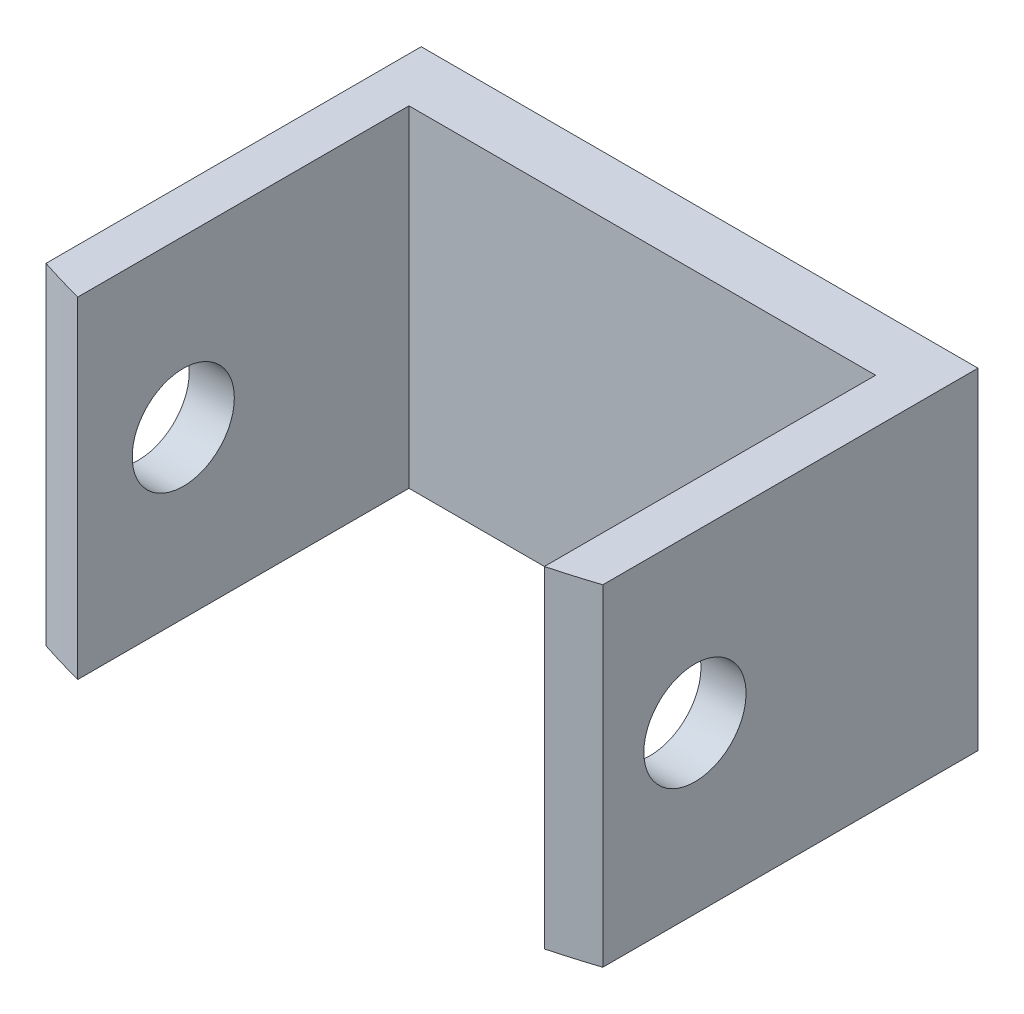
SolidWorks part; units mm, degrees
ref_plane "Front Plane" through (0, 0, 0) normal (0, 0, 1) x (1, 0, 0)
ref_plane "Top Plane" through (0, 0, 0) normal (0, 1, 0) x (1, 0, 0)
ref_plane "Right Plane" through (0, 0, 0) normal (1, 0, 0) x (0, 0, -1)
sketch "Sketch2" plane through (0, 0, 0) normal (0, 1, 0) x (1, 0, 0)
  line L0 (0, 0) -> (0, -76.2) construction
  line L1 (-38.1, -65.9911) -> (0, 0)
  line L2 (0, 0) -> (0, -76.2)
  arc A0 (0, -76.2) -> (-38.1, -65.9911) centre (0, 0) cw
  dimension "D1" = 76.2
extrude "Boss-Extrude1" add sketch "Sketch2" along normal blind 28
sketch "Sketch3" plane through (0, 0, 0) normal (0, 1, 0) x (1, 0, 0)
  line L0 (-38.1, -65.9911) -> (0, -76.2) construction
  line L7 (0, 0) -> (-19.05, -71.0956) construction
  line L8 (-19.05, -71.0956) -> (-19.722, -73.6035) construction
  line L10 (-19.722, -73.6035) -> (19.722, -73.6035) construction
  line L11 (19.722, -73.6035) -> (53.8815, -53.8815) construction
  line L12 (53.8815, -53.8815) -> (73.6035, -19.722) construction
  line L13 (73.6035, -19.722) -> (73.6035, 19.722) construction
  line L14 (73.6035, 19.722) -> (53.8815, 53.8815) construction
  line L15 (53.8815, 53.8815) -> (19.722, 73.6035) construction
  line L16 (19.722, 73.6035) -> (-19.722, 73.6035) construction
  line L17 (-19.722, 73.6035) -> (-53.8815, 53.8815) construction
  line L18 (-53.8815, 53.8815) -> (-73.6035, 19.722) construction
  line L19 (-73.6035, 19.722) -> (-73.6035, -19.722) construction
  line L20 (-73.6035, -19.722) -> (-53.8815, -53.8815) construction
  line L21 (-53.8815, -53.8815) -> (-19.722, -73.6035) construction
  circle A0 centre (0, 0) radius 76.2 construction
  circle A1 centre (0, 0) radius 76.2 construction
sketch "Sketch4" plane through (0, 28, 0) normal (0, 1, 0) x (1, 0, 0)
  line L2 (-19.722, -73.6035) -> (-19.722, -45.6036)
  line L3 (-19.722, -45.6036) -> (19.722, -45.6036)
  line L4 (19.722, -73.6035) -> (19.722, -45.6036)
  line L7 (-19.722, -73.6035) -> (-19.722, -89.0834)
  line L8 (-19.722, -89.0834) -> (19.722, -89.0834)
  line L9 (19.722, -73.6035) -> (19.722, -89.0834)
  dimension "D1" = 28
  dimension "D2" = 39.444
extrude "Cut-Extrude1" cut sketch "Sketch4" against normal through all both and the other way through all
sketch "Sketch5" plane through (-19.722, 0, 0) normal (1, 0, 0) x (0, 0, -1)
  line L0 (-73.6035, 28) -> (-45.6036, 0) construction
  line L1 (-45.6036, 28) -> (-73.6035, 0) construction
  line L3 (-59.6036, 14) -> (-64.6836, 14) construction
  circle A2 centre (-64.6836, 14) radius 6.35
  dimension "D2" = 12.7
  dimension "D1" = 5.08
extrude "Cut-Extrude2" cut sketch "Sketch5" against normal blind 4.572
sketch "Sketch6" plane through (-24.294, 0, 0) normal (1, 0, 0) x (0, 0, -1)
  line L0 (-68.3666, 14) -> (-68.4936, 14) construction
  line L1 (-71.0336, 14) -> (-70.7796, 14) construction
  line L2 (-64.6836, 17.81) -> (-64.6836, 20.096) construction
  line L3 (-64.6836, 14) -> (-45.6036, 14) construction
  line L4 (-45.6036, 0) -> (-45.6036, 28) construction
  line L5 (-64.6836, 14) -> (-61.7723, 18.0071) construction
  circle A0 centre (-64.6836, 14) radius 3.683
  circle A1 centre (-64.6836, 14) radius 3.81
  circle A2 centre (-64.6836, 14) radius 6.35 construction
  circle A3 centre (-64.6836, 14) radius 6.35 construction
  circle A4 centre (-64.6836, 14) radius 6.096
  circle A5 centre (-64.6836, 18.953) radius 1.143
  circle A6 centre (-61.7723, 18.0071) radius 1.143
  circle A7 centre (-59.973, 15.5306) radius 1.143
  circle A8 centre (-59.973, 12.4694) radius 1.143
  circle A9 centre (-61.7723, 9.9929) radius 1.143
  circle A10 centre (-64.6836, 9.047) radius 1.143
  circle A11 centre (-67.5949, 9.9929) radius 1.143
  circle A12 centre (-69.3941, 12.4694) radius 1.143
  circle A13 centre (-69.3941, 15.5306) radius 1.143
  circle A14 centre (-67.5949, 18.0071) radius 1.143
  point P38 (-64.6836, 14)
  dimension "D1" = 7.366
  dimension "D4" = 2.286
  dimension "D5" = 10
  dimension "D6" = 2.286
  dimension "D7" = 2.286
  dimension "D2" = 0.127
  dimension "D3" = 0.254
  dimension "D8" = 19.08
  dimension "D9" = 4.953
sketch "Sketch7" plane through (0, 0, 45.6036) normal (0, 0, 1) x (1, 0, 0)
  line L0 (-24.294, 14) -> (-21.5, 14) construction
  line L1 (-21.5, 14) -> (-19.722, 14) construction
  line L2 (-19.722, 0) -> (-19.722, 28) construction
  line L3 (-24.294, 14) -> (0, 14) construction
  line L4 (0, 28) -> (0, 0) construction
  dimension "D1" = 2.794
  dimension "D2" = 1.778
sketch "Sketch8" plane through (-19.722, 0, 0) normal (1, 0, 0) x (0, 0, -1)
  circle A0 centre (-64.6836, 14) radius 6.35
  circle A1 centre (-64.6836, 14) radius 4.318
  dimension "D1" = 8.636
extrude "Boss-Extrude4" add sketch "Sketch8" against normal blind 6.858
sketch "Sketch13" plane through (0, 0, 0) normal (0, 1, 0) x (1, 0, 0)
  line L0 (-19.722, -73.6035) -> (-19.722, -45.6036) construction
  line L1 (0, 0) -> (-23.532, -51.7) construction
  line L2 (-23.532, -79.498) -> (-59.7536, -79.498)
  line L3 (-23.532, -79.498) -> (-23.532, -51.7)
  line L5 (-59.7536, -79.498) -> (-59.7536, -51.7)
  line L6 (-23.532, -79.498) -> (-59.7536, -51.7) construction
  line L7 (-23.532, -51.7) -> (-59.7536, -79.498) construction
  line L11 (-9.525, -16.4978) -> (-28.4018, -49.1933) construction
  line L12 (0, 0) -> (-38.1, -65.9911) construction
  line L14 (-23.532, -51.7) -> (-28.4018, -49.1933) construction
  line L15 (0, 0) -> (-33.0075, -46.2293) construction
  line L17 (-33.0075, -46.2293) -> (-59.7536, -51.7)
  line L18 (-6.6467, -17.8528) -> (-17.2837, -36.2767)
  line L19 (-3.1702, -40.0584) -> (-3.1702, -18.7844)
  line L22 (-23.532, -51.7) -> (-23.532, -36.2767)
  line L23 (0, -45.6036) -> (0, 0) construction
  line L24 (-6.6467, -17.8528) -> (-17.2837, -36.2767) construction
  line L25 (-17.2837, -36.2767) -> (-10.7336, -40.0584)
  line L26 (-10.7336, -40.0584) -> (-3.1702, -40.0584)
  line L27 (-23.532, -36.2767) -> (-33.0075, -46.2293)
  arc A0 (-6.6467, -17.8528) -> (-3.1702, -18.7844) centre (0, 0) ccw
  point P5 (-41.6428, -65.599)
  dimension "D9" = 38.1
  dimension "D1" = 3.81
  dimension "D2" = 27.798
  dimension "D3" = 36.2216
  dimension "D4" = 56.8036
  dimension "D5" = 56.8036
  dimension "D6" = 5.4771
  dimension "D7" = 56.8036
  dimension "D8" = 5.4771
  dimension "D10" = 3.1702
  dimension "D11" = 3.1702
  dimension "D12" = 21.274
extrude "Cut-Extrude6" cut sketch "Sketch13" against normal blind 2.54 and the other way through all
sketch "Sketch14" plane through (0, 28, 0) normal (0, 1, 0) x (1, 0, 0)
  line L1 (-23.532, -40.7586) -> (28.3068, -40.7586)
  line L2 (-23.532, -40.7586) -> (-23.532, 5.356)
  line L3 (-23.532, 5.356) -> (28.3068, 5.356)
  line L4 (28.3068, -40.7586) -> (28.3068, 5.356)
  line L5 (-23.532, -40.7586) -> (28.3068, 5.356) construction
  line L6 (-23.532, 5.356) -> (28.3068, -40.7586) construction
  point P4 (2.3874, -17.7013)
extrude "Cut-Extrude7" cut sketch "Sketch14" against normal through all both and the other way through all
mirror "Mirror2" about plane through (0, 28, 0) normal (-1, 0, 0) of "Cut-Extrude1", "Cut-Extrude2", "Boss-Extrude4", "Cut-Extrude6", "Cut-Extrude7", "Boss-Extrude1"
